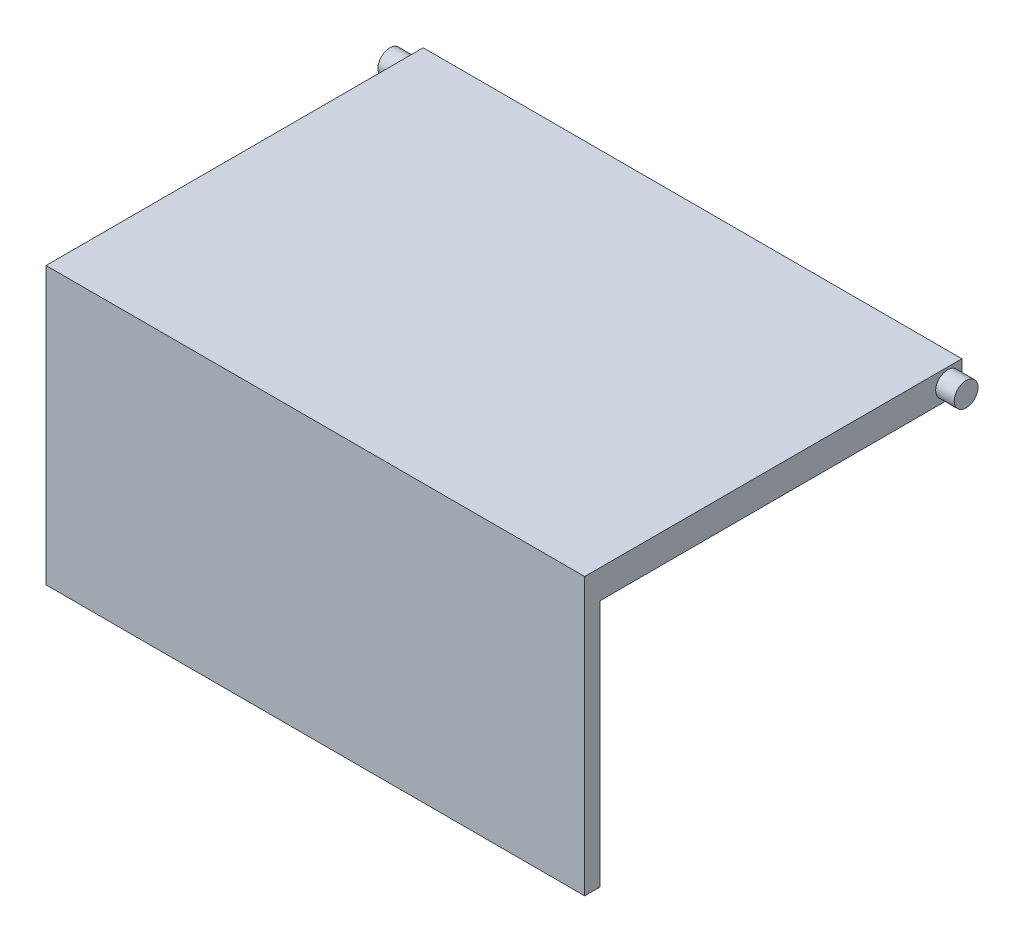
SolidWorks part; units mm, degrees
ref_plane "Front Plane" through (0, 0, 0) normal (0, 0, 1) x (1, 0, 0)
ref_plane "Top Plane" through (0, 0, 0) normal (0, 1, 0) x (1, 0, 0)
ref_plane "Right Plane" through (0, 0, 0) normal (1, 0, 0) x (0, 0, -1)
sketch "Sketch1" plane through (0, 0, 0) normal (0, 0, 1) x (1, 0, 0)
  line L1 (-22.3693, 8.5806) -> (90.7407, 8.5806)
  line L2 (-22.3693, 8.5806) -> (-22.3693, 3.5806)
  line L3 (-22.3693, 3.5806) -> (90.7407, 3.5806)
  line L4 (90.7407, 8.5806) -> (90.7407, 3.5806)
  dimension "D1" = 113.11
  dimension "D2" = 5
extrude "Boss-Extrude1" add sketch "Sketch1" along normal blind 80
sketch "Sketch2" plane through (0, 3.5806, 0) normal (0, -1, 0) x (1, 0, 0)
  line L0 (90.7407, 80) -> (90.7407, 0) construction
  line L1 (-22.3693, 80) -> (90.7407, 80)
  line L2 (-22.3693, 80) -> (-22.3693, 76)
  line L3 (-22.3693, 76) -> (90.7407, 76)
  line L4 (90.7407, 80) -> (90.7407, 76)
  dimension "D1" = 4
extrude "Boss-Extrude3" add sketch "Sketch2" along normal blind 53.07
sketch "Sketch3" plane through (-22.3693, 0, 0) normal (-1, 0, 0) x (0, 0, 1)
  line L0 (0, 8.5806) -> (0, 3.5806) construction
  line L1 (76, 3.5806) -> (0, 3.5806) construction
  circle A0 centre (3, 5.5806) radius 2.5
  dimension "D1" = 5
  dimension "D2" = 3
  dimension "D3" = 2
extrude "Boss-Extrude4" add sketch "Sketch3" against normal blind 117 and the other way blind 4 contours A0
sketch "Sketch4" plane through (0, 0, 0) normal (0, 0, -1) x (-1, 0, 0)
  line L0 (22.3693, -49.4894) -> (22.3693, 3.5806) construction
  line L1 (-90.7407, 3.5806) -> (22.3693, 3.5806)
  line L2 (-90.7407, 3.5806) -> (-90.7407, 2.5661)
  line L3 (-90.7407, 2.5661) -> (22.3693, 2.5661)
  line L4 (22.3693, 3.5806) -> (22.3693, 2.5661)
extrude "Boss-Extrude5" add sketch "Sketch4" against normal blind 79
sketch "Sketch5" plane through (-22.3693, 0, 0) normal (-1, 0, 0) x (0, 0, 1)
  line L1 (80, 8.5806) -> (79.2, 8.5806)
  line L2 (80, 8.5806) -> (80, -53.5195)
  line L3 (80, -53.5195) -> (79.2, -53.5195)
  line L4 (79.2, 8.5806) -> (79.2, -53.5195)
  dimension "D1" = 0.8
extrude "Cut-Extrude2" cut sketch "Sketch5" against normal blind 224
